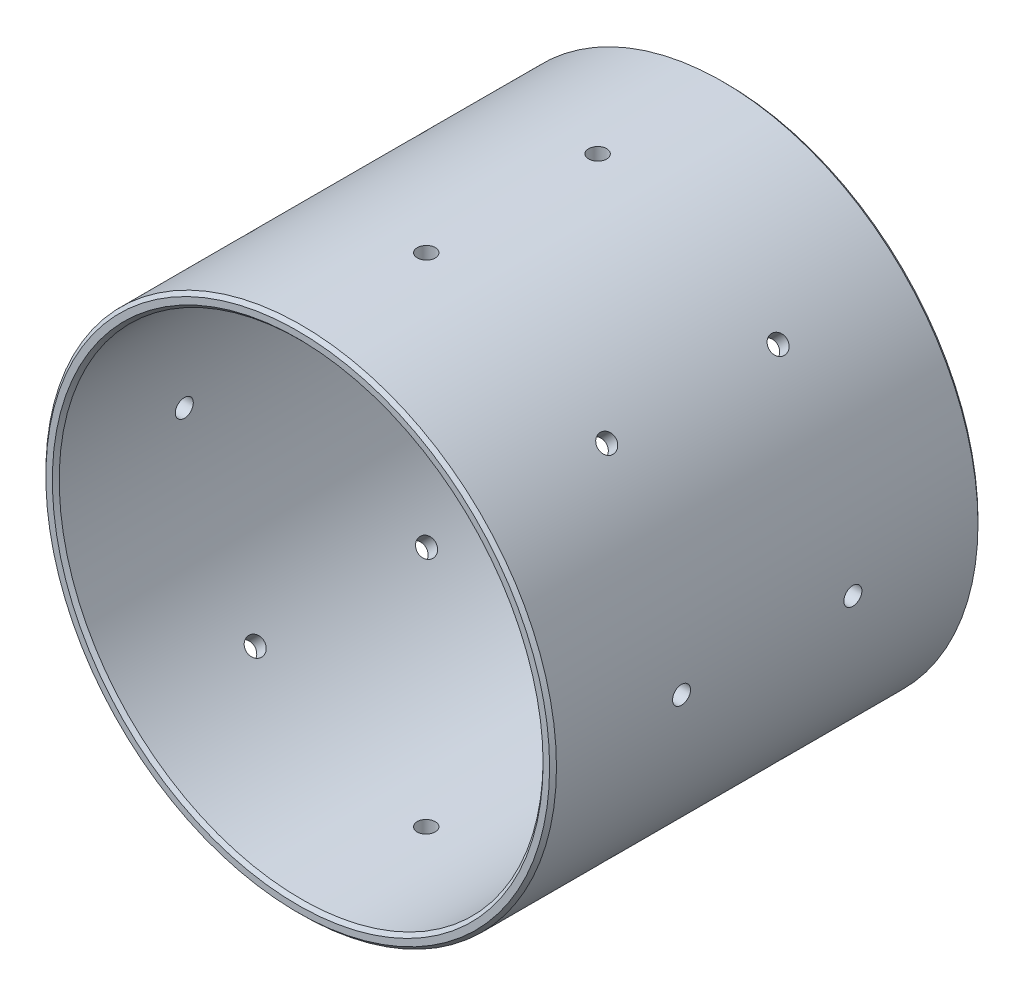
SolidWorks part; units mm, degrees
ref_plane "Front Plane" through (0, 0, 0) normal (1, 0, 0) x (0, 1, 0)
ref_plane "Top Plane" through (0, 0, 0) normal (0, 0, 1) x (0, 1, 0)
ref_plane "Right Plane" through (0, 0, 0) normal (0, 1, 0) x (-1, 0, 0)
sketch "Sketch1" plane through (0, 0, 0) normal (0, 0, 1) x (0, 1, 0)
  circle A0 centre (0, 0) radius 29.8
  dimension "D1" = 59.6
extrude "Extrude-Thin1" add sketch "Sketch1" along normal blind 50 thin thin type one direction reverse wall 1.56
chamfer "Chamfer1" distance 0.4 angle 45 4 edges at (0, 28.24, 50) (0, 28.24, 0) (29.8, 0, 0) (29.8, 0, 50)
sketch "Sketch2" plane through (0, 0, 0) normal (0, 1, 0) x (-1, 0, 0)
  line L0 (28.64, 50) -> (-28.64, 50) construction
  circle A0 centre (0, 35) radius 1.05
  circle A1 centre (0, 15) radius 1.05
  point P6 (0, 0)
  point P8 (0, 0)
  point P9 (0, 0)
  dimension "D1" = 2.1
  dimension "D3" = 2.1
  dimension "D2" = 15
  dimension "D4" = 20
extrude "Cut-Extrude1" cut sketch "Sketch2" against normal through all both and the other way through all contours A0 | A1
pattern_circular "CirPattern1" count 4 every 45 about axis through (0, 0, 50) along (0, 0, -1) of "Cut-Extrude1"
